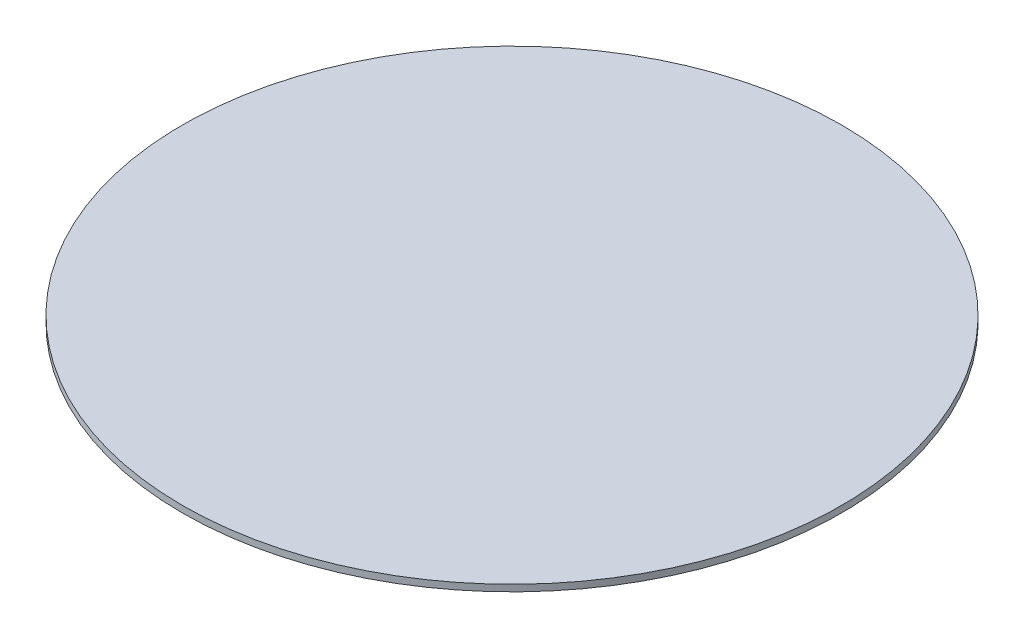
SolidWorks part; units mm, degrees
ref_plane "Front Plane" through (0, 0, 0) normal (0, 0, 1) x (1, 0, 0)
ref_plane "Top Plane" through (0, 0, 0) normal (0, 1, 0) x (1, 0, 0)
ref_plane "Right Plane" through (0, 0, 0) normal (1, 0, 0) x (0, 0, -1)
sketch "Sketch1" plane through (0, 0, 0) normal (0, 1, 0) x (1, 0, 0)
  circle A0 centre (0, 0) radius 40
  dimension "D1" = 80
extrude "Boss-Extrude1" add sketch "Sketch1" along normal blind 0.8
